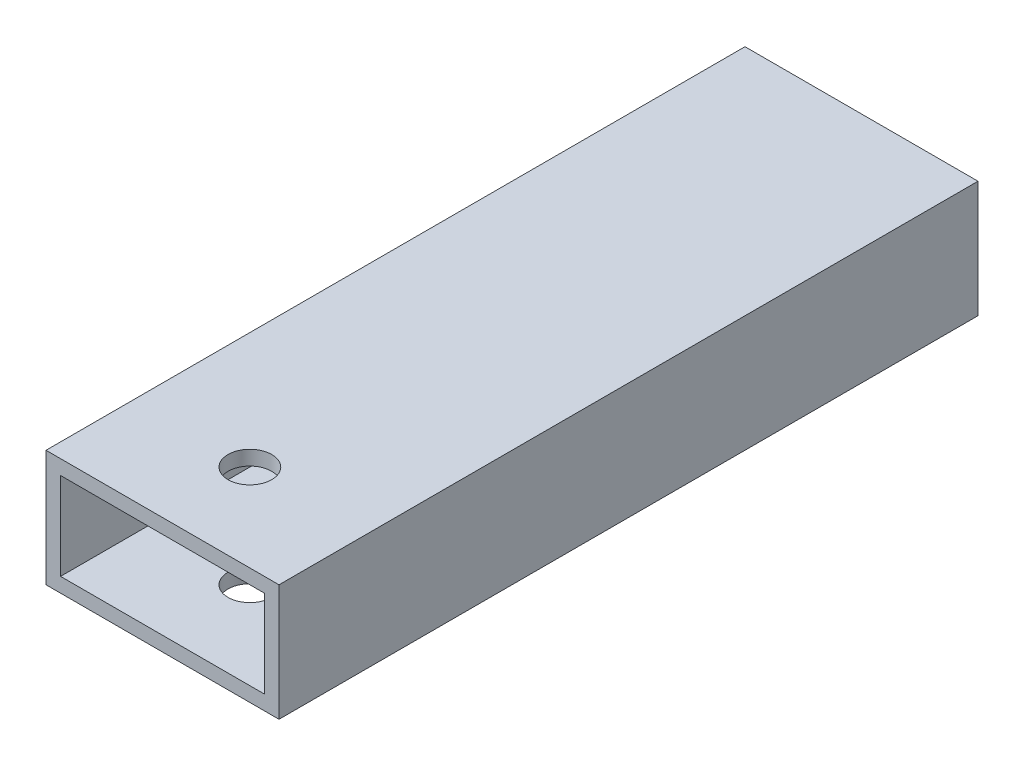
SolidWorks part; units mm, degrees
ref_plane "Front Plane" through (0, 0, 0) normal (0, 0, 1) x (1, 0, 0)
ref_plane "Top Plane" through (0, 0, 0) normal (0, 1, 0) x (1, 0, 0)
ref_plane "Right Plane" through (0, 0, 0) normal (1, 0, 0) x (0, 0, -1)
sketch "Sketch1" plane through (0, 0, 0) normal (0, 0, 1) x (1, 0, 0)
  line L0 (-22.225, -9.525) -> (22.225, -9.525)
  line L1 (-25.4, -12.7) -> (25.4, -12.7)
  line L2 (-25.4, -12.7) -> (-25.4, 12.7)
  line L3 (-25.4, 12.7) -> (25.4, 12.7)
  line L4 (25.4, -12.7) -> (25.4, 12.7)
  line L5 (22.225, -9.525) -> (22.225, 9.525)
  line L6 (-22.225, 9.525) -> (22.225, 9.525)
  line L7 (-22.225, -9.525) -> (-22.225, 9.525)
  dimension "D1" = 25.4
  dimension "D2" = 50.8
  dimension "D3" = 3.175
extrude "Boss-Extrude1" add sketch "Sketch1" along normal blind 152.4
sketch "Sketch2" plane through (0, 12.7, 0) normal (0, 1, 0) x (1, 0, 0)
  circle A1 centre (0, -133.35) radius 4.7625
extrude "Cut-Extrude1" cut sketch "Sketch2" against normal through all
